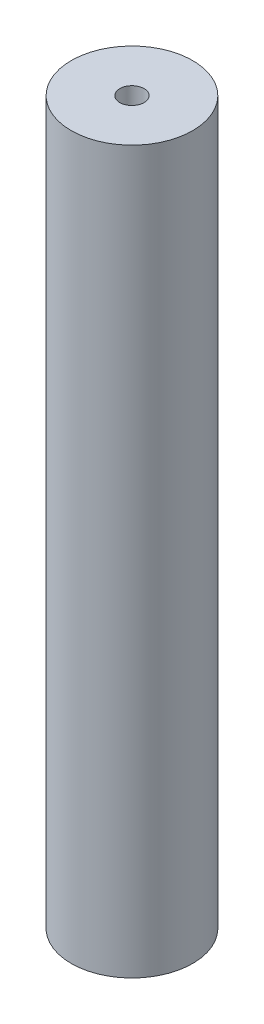
SolidWorks part; units mm, degrees
ref_plane "Front Plane" through (0, 0, 0) normal (0, 0, 1) x (1, 0, 0)
ref_plane "Top Plane" through (0, 0, 0) normal (0, 1, 0) x (1, 0, 0)
ref_plane "Right Plane" through (0, 0, 0) normal (1, 0, 0) x (0, 0, -1)
sketch "Sketch1" plane through (0, 0, 0) normal (0, 1, 0) x (1, 0, 0)
  circle A0 centre (0, 0) radius 8
extrude "Boss-Extrude1" add sketch "Sketch1" along normal blind 95 contours A0
sketch "Sketch2" plane through (0, 0, 0) normal (0, -1, 0) x (1, 0, 0)
  circle A0 centre (0, 0) radius 1.6
extrude "Cut-Extrude1" cut sketch "Sketch2" against normal blind 95
